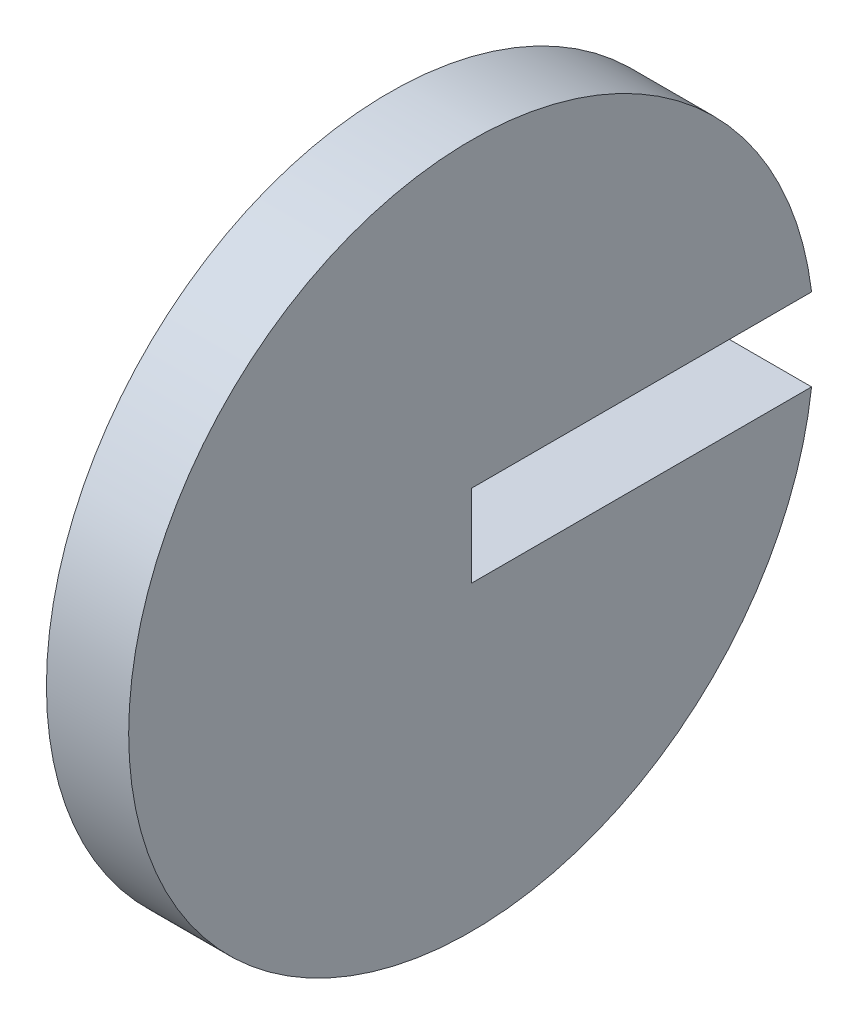
SolidWorks part; units mm, degrees
ref_plane "Front Plane" through (0, 0, 0) normal (0, 0, 1) x (1, 0, 0)
ref_plane "Top Plane" through (0, 0, 0) normal (0, 1, 0) x (1, 0, 0)
ref_plane "Right Plane" through (0, 0, 0) normal (1, 0, 0) x (0, 0, -1)
sketch "Sketch1" plane through (0, 0, 0) normal (1, 0, 0) x (0, 0, -1)
  circle A0 centre (0, 0) radius 12.5
  dimension "D1" = 25
extrude "Boss-Extrude1" add sketch "Sketch1" along normal blind 3
sketch "Sketch2" plane through (3, 0, 0) normal (1, 0, 0) x (0, 0, -1)
  line L0 (-20.0093, 0) -> (20.0093, 0) construction
  line L2 (0, -1.5) -> (25, -1.5)
  line L3 (0, -1.5) -> (0, 1.5)
  line L4 (0, 1.5) -> (25, 1.5)
  line L5 (25, -1.5) -> (25, 1.5)
  line L6 (0, -1.5) -> (25, 1.5) construction
  line L7 (0, 1.5) -> (25, -1.5) construction
  circle A0 centre (0, 0) radius 12.5 construction
  point P0 (12.5, 0)
  point P5 (0, 0)
  dimension "D1" = 3
  dimension "D2" = 25
extrude "Cut-Extrude1" cut sketch "Sketch2" against normal blind 3
